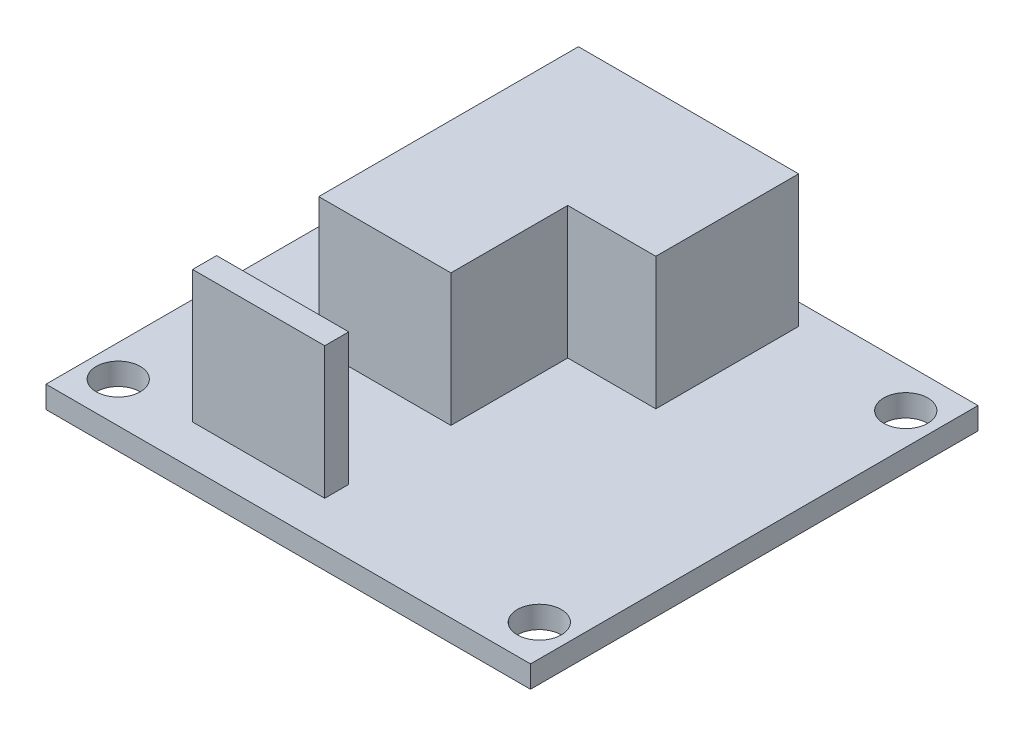
SolidWorks part; units mm, degrees
ref_plane "Front" through (0, 0, 0) normal (0, 0, 1) x (1, 0, 0)
ref_plane "Top" through (0, 0, 0) normal (0, 1, 0) x (1, 0, 0)
ref_plane "Right" through (0, 0, 0) normal (1, 0, 0) x (0, 0, -1)
sketch "Sketch2" plane through (0, 0, 0) normal (0, 1, 0) x (1, 0, 0)
  line L0 (0, -55) -> (0, 55) construction
  line L1 (-17.4625, 16.129) -> (17.4625, 16.129)
  line L2 (-17.4625, 16.129) -> (-17.4625, -16.129)
  line L3 (-17.4625, -16.129) -> (17.4625, -16.129)
  line L4 (17.4625, 16.129) -> (17.4625, -16.129)
  line L5 (-17.4625, 16.129) -> (17.4625, -16.129) construction
  line L6 (-17.4625, -16.129) -> (17.4625, 16.129) construction
  line L7 (-55, 0) -> (55, 0) construction
  line L9 (-9.8168, 14.6038) -> (-0.2918, 14.6038)
  line L10 (-9.8168, 14.6038) -> (-9.8168, -4.1127)
  line L11 (-9.8168, -4.1127) -> (-0.2918, -4.1127)
  line L12 (-0.2918, 14.6038) -> (-0.2918, -4.1127)
  line L13 (-0.2918, 14.6038) -> (6.0582, 14.6038)
  line L14 (-0.2918, 14.6038) -> (-0.2918, 4.3097)
  line L15 (-0.2918, 4.3097) -> (6.0582, 4.3097)
  line L16 (6.0582, 14.6038) -> (6.0582, 4.3097)
  line L17 (-9.8168, -11.4774) -> (-0.2918, -11.4774)
  line L18 (-9.8168, -11.4774) -> (-9.8168, -13.208)
  line L19 (-9.8168, -13.208) -> (-0.2918, -13.208)
  line L20 (-0.2918, -11.4774) -> (-0.2918, -13.208)
  circle A0 centre (-15.1765, 13.208) radius 1.5875
  circle A1 centre (15.1765, 13.208) radius 1.5875
  circle A2 centre (15.1765, -13.208) radius 1.5875
  circle A3 centre (-15.1765, -13.208) radius 1.5875
  point P0 (0, 0)
  dimension "D3" = 3.175
  dimension "D1" = 34.925
  dimension "D2" = 32.258
  dimension "D4" = 2.921
  dimension "D5" = 2.286
  dimension "D6" = 15.875
  dimension "D7" = 9.525
  dimension "D8" = 6.35
extrude "Boss-Extrude1" add sketch "Sketch2" along normal blind 1.5875 contours L4 L1 L2 L3 A1 A0 L13 L16 L15 L12 L11 L10 L9 L17 L20 L19 L18 A2 A3
sketch "Sketch3" plane through (0, 1.5875, 0) normal (0, 1, 0) x (1, 0, 0)
  line L0 (-9.8168, 14.6038) -> (6.0582, 14.6038) construction
  line L1 (-9.8168, 14.6038) -> (-9.8168, -4.1127) construction
  line L2 (-9.8168, -4.1127) -> (-0.2918, -4.1127) construction
  line L3 (-0.2918, 4.3097) -> (-0.2918, -4.1127) construction
  line L4 (17.4625, -16.129) -> (17.4625, 16.129)
  line L5 (17.4625, 16.129) -> (-17.4625, 16.129)
  line L6 (-17.4625, 16.129) -> (-17.4625, -16.129)
  line L7 (-17.4625, -16.129) -> (17.4625, -16.129)
  line L8 (17.4625, -16.129) -> (17.4625, 16.129)
  line L9 (17.4625, 16.129) -> (-17.4625, 16.129)
  line L10 (-17.4625, 16.129) -> (-17.4625, -16.129)
  line L11 (-17.4625, -16.129) -> (17.4625, -16.129)
  line L12 (-0.2918, 4.3097) -> (6.0582, 4.3097) construction
  line L13 (6.0582, 14.6038) -> (6.0582, 4.3097) construction
  line L14 (-0.2918, -11.4774) -> (-0.2918, -13.208) construction
  line L15 (-9.8168, -11.4774) -> (-0.2918, -11.4774) construction
  line L16 (-9.8168, -11.4774) -> (-9.8168, -13.208) construction
  line L17 (-9.8168, -13.208) -> (-0.2918, -13.208) construction
  line L18 (-9.8168, -13.208) -> (-0.2918, -13.208)
  line L19 (-9.8168, -11.4774) -> (-9.8168, -13.208)
  line L20 (-9.8168, -11.4774) -> (-0.2918, -11.4774)
  line L21 (-0.2918, -11.4774) -> (-0.2918, -13.208)
  line L22 (6.0582, 14.6038) -> (6.0582, 4.3097)
  line L23 (-0.2918, 4.3097) -> (6.0582, 4.3097)
  line L24 (-0.2918, 4.3097) -> (-0.2918, -4.1127)
  line L25 (-9.8168, -4.1127) -> (-0.2918, -4.1127)
  line L26 (-9.8168, 14.6038) -> (-9.8168, -4.1127)
  line L27 (-9.8168, 14.6038) -> (6.0582, 14.6038)
  line M21 (-9.8168, 14.6038) -> (6.0582, 14.6038)
  line M22 (6.0582, 14.6038) -> (6.0582, 4.3097)
  line M23 (6.0582, 4.3097) -> (-0.2918, 4.3097)
  line M24 (-0.2918, 4.3097) -> (-0.2918, -4.1127)
  line M25 (-0.2918, -4.1127) -> (-9.8168, -4.1127)
  line M26 (-9.8168, -4.1127) -> (-9.8168, 14.6038)
  line M27 (-9.8168, -11.4774) -> (-0.2918, -11.4774)
  line M28 (-0.2918, -11.4774) -> (-0.2918, -13.208)
  line M29 (-0.2918, -13.208) -> (-9.8168, -13.208)
  line M30 (-9.8168, -13.208) -> (-9.8168, -11.4774)
  dimension "D1" = 0
extrude "Boss-Extrude2" add sketch "Sketch3" along normal blind 9.525 separate body contours M21 M26 M25 M24 M23 M22 | M27 M30 M29 M28
